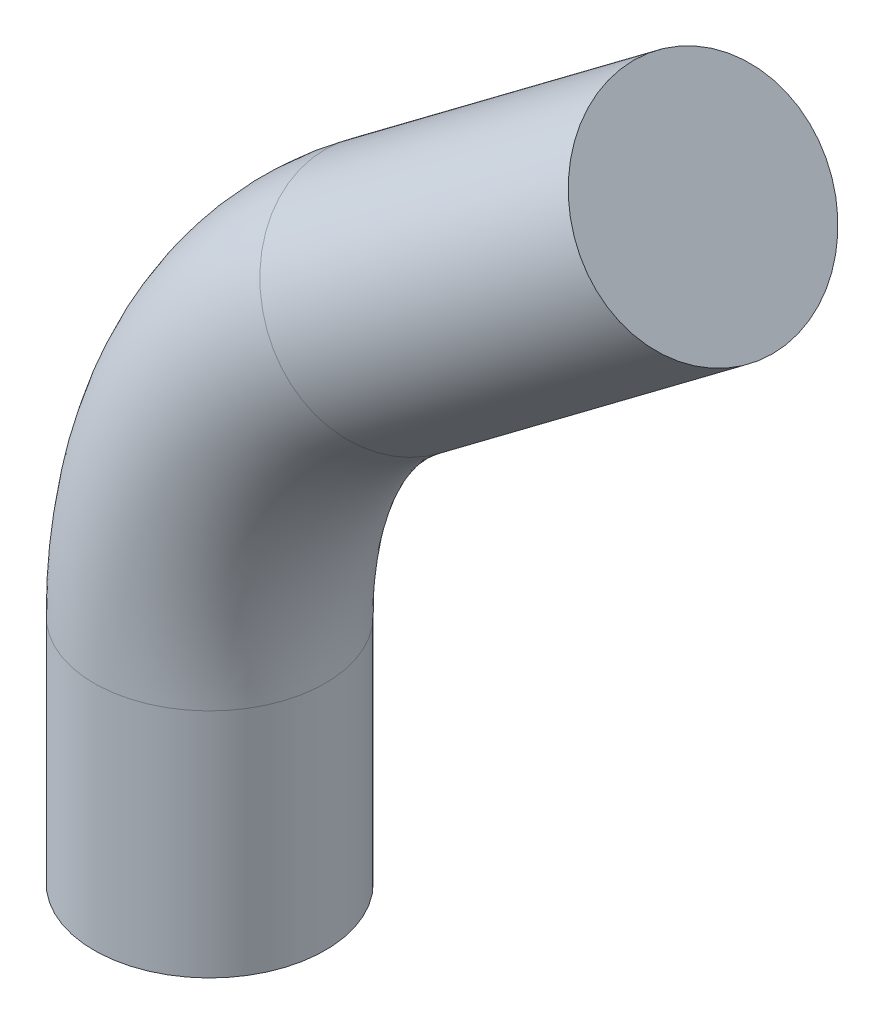
SolidWorks part; units mm, degrees
ref_plane "Front Plane" through (0, 0, 0) normal (0, 0, 1) x (1, 0, 0)
ref_plane "Top Plane" through (0, 0, 0) normal (0, 1, 0) x (1, 0, 0)
ref_plane "Right Plane" through (0, 0, 0) normal (1, 0, 0) x (0, 0, -1)
sketch "Sketch1" plane through (0, 0, 0) normal (0, 0, 1) x (1, 0, 0)
  line L0 (0, -5) -> (0, -10)
  line L1 (4, 3) -> (10.6667, 8)
  arc A0 (0, -5) -> (4, 3) centre (10, -5) cw
  point P6 (0, 0)
  dimension "D3" = 10
  dimension "D1" = 10
  dimension "D2" = 8
  dimension "D4" = 5
sweep "Sweep1" add path "Sketch1" circular profile diameter 5 parameters "D3"=5
scale "Scale1" scale about origin uniform scaling yes scale factor 3
